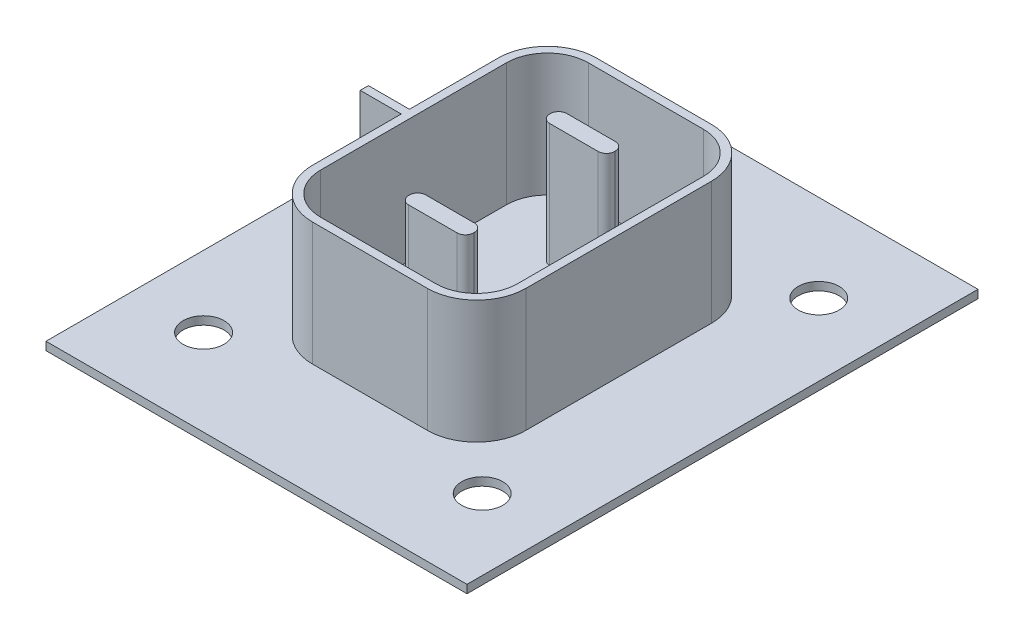
SolidWorks part; units mm, degrees
ref_plane "前视基准面" through (0, 0, 0) normal (0, 0, 1) x (1, 0, 0)
ref_plane "上视基准面" through (0, 0, 0) normal (0, 1, 0) x (1, 0, 0)
ref_plane "右视基准面" through (0, 0, 0) normal (1, 0, 0) x (0, 0, -1)
sketch "草图1" plane through (0, 0, 0) normal (0, 1, 0) x (1, 0, 0)
  line L0 (-14.0112, 34.6331) -> (14.0112, 34.6331)
  line L1 (-14.0112, 32.6331) -> (14.0112, 32.6331)
  line L2 (-24.0112, 22.6331) -> (-24.0112, -22.6331)
  line L3 (-14.0112, -32.6331) -> (14.0112, -32.6331)
  line L4 (24.0112, 22.6331) -> (24.0112, -22.6331)
  line L5 (-24.0112, 32.6331) -> (24.0112, -32.6331) construction
  line L6 (-24.0112, -32.6331) -> (24.0112, 32.6331) construction
  line L7 (26.0112, 22.6331) -> (26.0112, -22.6331)
  line L8 (-14.0112, -34.6331) -> (14.0112, -34.6331)
  line L9 (-26.0112, 22.6331) -> (-26.0112, 1)
  line L10 (-26.0112, -1) -> (-26.0112, -22.6331)
  line L11 (-26.0112, 1) -> (-36.0112, 1)
  line L12 (-7.9084, 0) -> (14.0112, 0) construction
  line L13 (-26.0112, -1) -> (-36.0112, -1)
  line L14 (-36.0112, 1) -> (-36.0112, -1)
  line L15 (-26.0112, 1) -> (-36.0112, -1) construction
  line L16 (-26.0112, -1) -> (-36.0112, 1) construction
  line L17 (-5.9084, 19.2914) -> (5.9084, 19.2914)
  line L18 (-26.0112, 22.6331) -> (-26.0112, -22.6331) construction
  line L19 (-7.9084, 17.2914) -> (-7.9084, 17.0991)
  line L20 (-5.9084, 15.0991) -> (5.9084, 15.0991)
  line L21 (7.9084, 17.2914) -> (7.9084, 17.0991)
  line L22 (-7.9084, 19.2914) -> (7.9084, 15.0991) construction
  line L23 (-7.9084, 15.0991) -> (7.9084, 19.2914) construction
  line L24 (-7.9084, -15.0991) -> (7.9084, -19.2914) construction
  line L25 (-7.9084, -19.2914) -> (7.9084, -15.0991) construction
  line L26 (7.9084, -17.2914) -> (7.9084, -17.0991)
  line L27 (-5.9084, -15.0991) -> (5.9084, -15.0991)
  line L28 (-7.9084, -17.2914) -> (-7.9084, -17.0991)
  line L29 (-5.9084, -19.2914) -> (5.9084, -19.2914)
  arc A0 (-14.0112, -32.6331) -> (-24.0112, -22.6331) centre (-14.0112, -22.6331) cw
  arc A1 (14.0112, -32.6331) -> (24.0112, -22.6331) centre (14.0112, -22.6331) ccw
  arc A2 (24.0112, 22.6331) -> (14.0112, 32.6331) centre (14.0112, 22.6331) ccw
  arc A3 (-24.0112, 22.6331) -> (-14.0112, 32.6331) centre (-14.0112, 22.6331) cw
  arc A4 (26.0112, 22.6331) -> (14.0112, 34.6331) centre (14.0112, 22.6331) ccw
  arc A5 (14.0112, -34.6331) -> (26.0112, -22.6331) centre (14.0112, -22.6331) ccw
  arc A6 (-14.0112, -34.6331) -> (-26.0112, -22.6331) centre (-14.0112, -22.6331) cw
  arc A7 (-26.0112, 22.6331) -> (-14.0112, 34.6331) centre (-14.0112, 22.6331) cw
  arc A8 (-7.9084, 17.2914) -> (-5.9084, 19.2914) centre (-5.9084, 17.2914) cw
  arc A9 (-7.9084, 17.0991) -> (-5.9084, 15.0991) centre (-5.9084, 17.0991) ccw
  arc A10 (5.9084, 15.0991) -> (7.9084, 17.0991) centre (5.9084, 17.0991) ccw
  arc A11 (5.9084, 19.2914) -> (7.9084, 17.2914) centre (5.9084, 17.2914) cw
  arc A12 (5.9084, -19.2914) -> (7.9084, -17.2914) centre (5.9084, -17.2914) ccw
  arc A13 (5.9084, -15.0991) -> (7.9084, -17.0991) centre (5.9084, -17.0991) cw
  arc A14 (-7.9084, -17.0991) -> (-5.9084, -15.0991) centre (-5.9084, -17.0991) cw
  arc A15 (-7.9084, -17.2914) -> (-5.9084, -19.2914) centre (-5.9084, -17.2914) ccw
  point P0 (0, 0)
  point P34 (-31.0112, 0)
  point P35 (0, 17.1953)
  point P70 (0, -17.1953)
  dimension "D1" = 10
  dimension "D5" = 2
  dimension "D2" = 2
  dimension "D3" = 10
  dimension "D4" = 2
extrude "凸台-拉伸1" add sketch "草图1" along normal blind 30 contours A7 L9 L11 L14 L13 L10 A6 L8 A5 L7 A4 L0 L2 A3 L1 A2 L4 A1 L3 A0 | A11 L17 A8 L19 A9 L20 A10 L21 | L28 A15 L29 A12 L26 A13 L27 A14
sketch "草图2" plane through (0, 0, 0) normal (0, 1, 0) x (1, 0, 0)
  line L1 (-51.3344, 62.3066) -> (51.3344, 62.3066)
  line L2 (-51.3344, 62.3066) -> (-51.3344, -62.3066)
  line L3 (-51.3344, -62.3066) -> (51.3344, -62.3066)
  line L4 (51.3344, 62.3066) -> (51.3344, -62.3066)
  line L5 (-51.3344, 62.3066) -> (51.3344, -62.3066) construction
  line L6 (-51.3344, -62.3066) -> (51.3344, 62.3066) construction
  circle A0 centre (-33.978, -41.2405) radius 5
  circle A1 centre (34.0024, -41.2701) radius 5
  circle A2 centre (33.7886, 41.0106) radius 5
  circle A3 centre (-33.5912, 40.771) radius 5
  point P0 (0, 0)
extrude "凸台-拉伸2" add sketch "草图2" against normal blind 2
